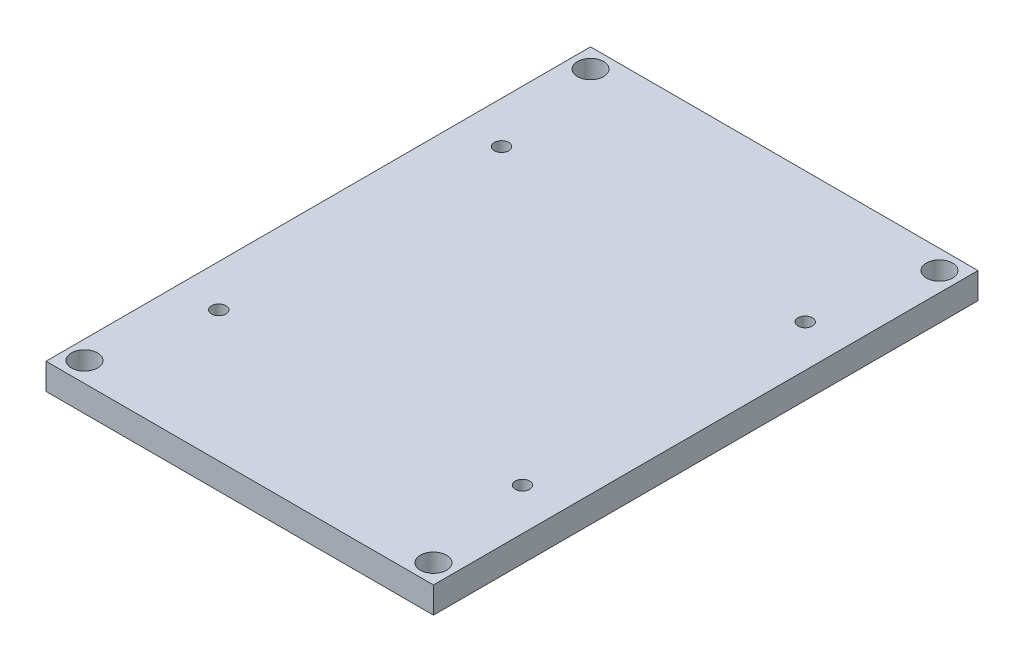
SolidWorks part; units mm, degrees
ref_plane "Front Plane" through (0, 0, 0) normal (0, 0, 1) x (1, 0, 0)
ref_plane "Top Plane" through (0, 0, 0) normal (0, 1, 0) x (1, 0, 0)
ref_plane "Right Plane" through (0, 0, 0) normal (1, 0, 0) x (0, 0, -1)
sketch "Sketch1" plane through (0, 0, 0) normal (0, 1, 0) x (1, 0, 0)
  line L0 (39.37, -58.42) -> (39.37, 58.42) construction
  line L1 (-46.99, -66.04) -> (46.99, -66.04)
  line L2 (-46.99, -66.04) -> (-46.99, 66.04)
  line L3 (-46.99, 66.04) -> (46.99, 66.04)
  line L4 (46.99, -66.04) -> (46.99, 66.04)
  line L5 (-46.99, -66.04) -> (46.99, 66.04) construction
  line L6 (-46.99, 66.04) -> (46.99, -66.04) construction
  line L7 (39.37, 58.42) -> (-39.37, 58.42) construction
  line L8 (-39.37, 58.42) -> (-39.37, -58.42) construction
  line L9 (-39.37, -58.42) -> (39.37, -58.42) construction
  line L10 (-39.37, 58.42) -> (-33.6226, 52.6726) construction
  line L11 (39.37, 58.42) -> (33.6226, 52.6726) construction
  line L12 (-39.37, -58.42) -> (-33.6226, -52.6726) construction
  line L13 (39.37, -58.42) -> (33.6226, -52.6726) construction
  circle A0 centre (-33.6226, 52.6726) radius 2.54
  circle A1 centre (33.6226, 52.6726) radius 2.54
  circle A2 centre (-33.6226, -52.6726) radius 2.54
  circle A3 centre (33.6226, -52.6726) radius 2.54
  point P0 (0, 0)
  dimension "D8" = 5.08
  dimension "D10" = 5.08
  dimension "D12" = 5.08
  dimension "D13" = 5.08
  dimension "D1" = 93.98
  dimension "D2" = 132.08
  dimension "D3" = 78.74
  dimension "D4" = 116.84
  dimension "D5" = 58.42
  dimension "D6" = 39.37
  dimension "D7" = 8.128
  dimension "D9" = 8.128
  dimension "D11" = 8.128
extrude "Boss-Extrude2" add sketch "Sketch1" along normal blind 6.35 contours L2 L1 L4 L3
sketch "Sketch2" plane through (0, 6.35, 0) normal (0, 1, 0) x (1, 0, 0)
  line L0 (39.37, 58.42) -> (39.37, -58.42) construction
  line L1 (39.37, -58.42) -> (-39.37, -58.42) construction
  line L2 (-39.37, -58.42) -> (-39.37, 58.42) construction
  line L3 (-39.37, 58.42) -> (39.37, 58.42) construction
  line L4 (-46.99, 66.04) -> (-42.3203, 61.3703) construction
  line L5 (46.99, 66.04) -> (42.3203, 61.3703) construction
  line L6 (-39.37, -58.42) -> (-42.4893, -61.2071) construction
  line L7 (46.99, -66.04) -> (42.3203, -61.3703) construction
  line L8 (-46.99, -66.04) -> (-42.4893, -61.2071) construction
  line L9 (-46.99, -66.04) -> (-46.99, 66.04) construction
  line L10 (39.37, 58.42) -> (42.3203, 61.3703) construction
  circle A0 centre (-42.3203, 61.3703) radius 3.175
  circle A1 centre (42.3203, 61.3703) radius 3.175
  circle A2 centre (-42.4893, -61.2071) radius 3.175
  circle A3 centre (42.3203, -61.3703) radius 3.175
  dimension "D6" = 6.35
  dimension "D7" = 6.35
  dimension "D8" = 6.35
  dimension "D9" = 6.35
  dimension "D11" = 6.604
  dimension "D1" = 78.74
  dimension "D2" = 116.84
  dimension "D3" = 58.42
  dimension "D4" = 39.37
  dimension "D5" = 6.604
  dimension "D10" = 6.604
  dimension "D12" = 45
extrude "Cut-Extrude1" cut sketch "Sketch2" against normal blind 6.35
sketch "Sketch3" plane through (0, 6.35, 0) normal (0, 1, 0) x (1, 0, 0)
  line L0 (-46.99, -66.04) -> (-46.99, 66.04) construction
  line L1 (-46.99, 66.04) -> (46.99, 66.04) construction
  line L2 (46.99, -66.04) -> (46.99, 66.04) construction
  line L3 (-46.99, -66.04) -> (46.99, -66.04) construction
  circle A0 centre (-36.83, 34.29) radius 1.7526
  circle A1 centre (36.83, 34.29) radius 1.7526
  circle A2 centre (-36.83, -34.29) radius 1.7526
  circle A3 centre (36.83, -34.29) radius 1.7526
  dimension "D1" = 3.5052
  dimension "D2" = 10.16
  dimension "D4" = 3.5052
  dimension "D5" = 31.75
  dimension "D6" = 10.16
  dimension "D7" = 3.5052
  dimension "D8" = 10.16
  dimension "D9" = 31.75
  dimension "D10" = 3.5052
  dimension "D3" = 31.75
  dimension "D11" = 31.75
  dimension "D12" = 10.16
extrude "Cut-Extrude2" cut sketch "Sketch3" against normal blind 6.35
